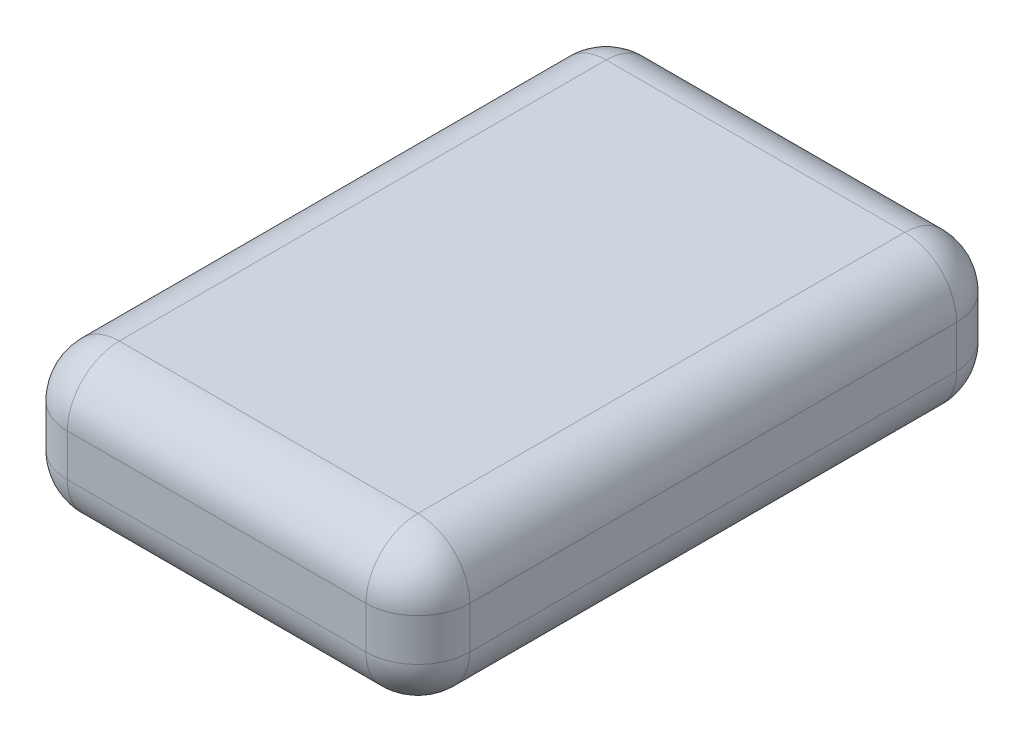
SolidWorks part; units mm, degrees
ref_plane "Front Plane" through (0, 0, 0) normal (0, 0, 1) x (1, 0, 0)
ref_plane "Top Plane" through (0, 0, 0) normal (0, 1, 0) x (1, 0, 0)
ref_plane "Right Plane" through (0, 0, 0) normal (1, 0, 0) x (0, 0, -1)
sketch "Sketch1" plane through (0, 0, 0) normal (0, 1, 0) x (1, 0, 0)
  line L1 (-31, 45.5) -> (31, 45.5)
  line L2 (-31, 45.5) -> (-31, -45.5)
  line L3 (-31, -45.5) -> (31, -45.5)
  line L4 (31, 45.5) -> (31, -45.5)
  line L5 (-31, 45.5) -> (31, -45.5) construction
  line L6 (-31, -45.5) -> (31, 45.5) construction
  point P0 (0, 0)
  dimension "D1" = 91
  dimension "D2" = 62
extrude "Boss-Extrude1" add sketch "Sketch1" along normal blind 22.5
fillet "Fillet1" radius 8 12 edges at (0, 0, 45.5) (31, 0, 0) (-31, 0, 0) (0, 0, -45.5) (0, 22.5, -45.5) (31, 22.5, 0) (31, 11.25, -45.5) (31, 11.25, 45.5) (-31, 22.5, 0) (-31, 11.25, 45.5) (0, 22.5, 45.5) (-31, 11.25, -45.5)
